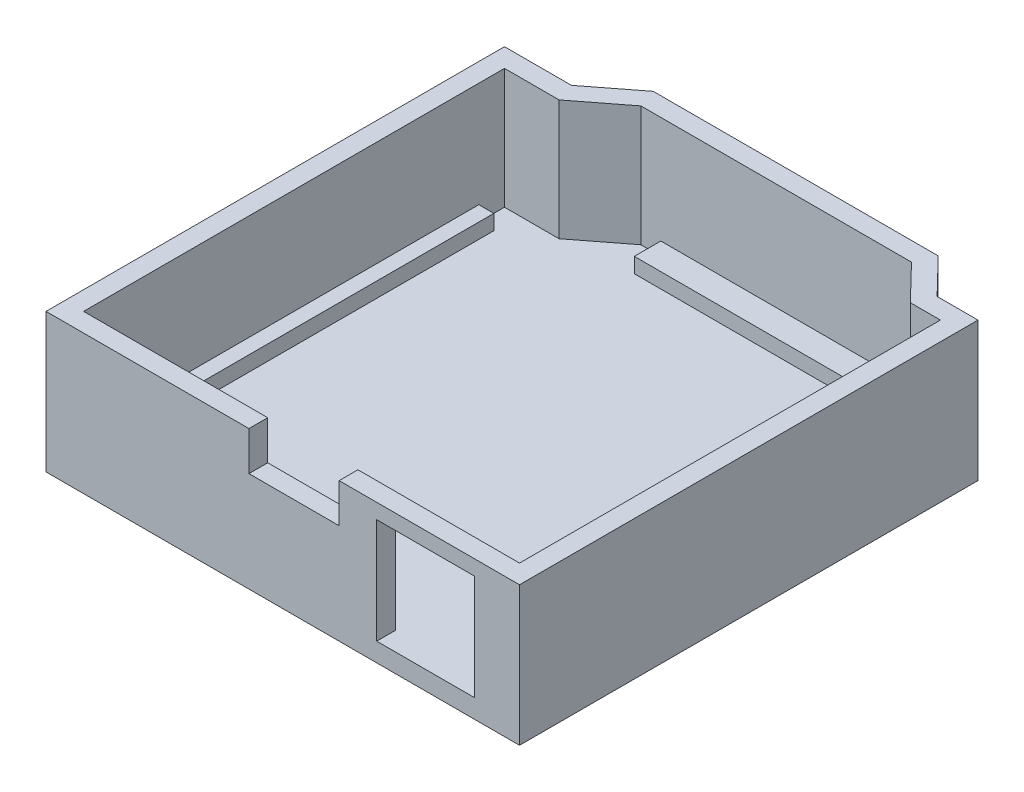
SolidWorks part; units mm, degrees
ref_plane "Front Plane" through (0, 0, 0) normal (0, 0, 1) x (1, 0, 0)
ref_plane "Top Plane" through (0, 0, 0) normal (0, 1, 0) x (1, 0, 0)
ref_plane "Right Plane" through (0, 0, 0) normal (1, 0, 0) x (0, 0, -1)
sketch "Sketch1" plane through (0, 0, 0) normal (0, 1, 0) x (1, 0, 0)
  line L0 (0, 0) -> (0, 56)
  line L1 (0, 56) -> (7.2606, 56)
  line L2 (7.2606, 56) -> (13.3994, 60.7502)
  line L3 (13.3994, 60.7502) -> (49.3994, 60.7502)
  line L4 (0, 0) -> (58, 0)
  line L5 (58, 0) -> (58, 56)
  line L7 (58, 56) -> (54, 56)
  line L8 (54, 56) -> (49.3994, 60.7502)
  point P8 (7.2606, 56)
  point P10 (13.3994, 60.7502)
  dimension "D1" = 56
  dimension "D2" = 58
  dimension "D3" = 4
  dimension "D4" = 36
extrude "Boss-Extrude1" add sketch "Sketch1" along normal blind 16
shell "Shell1" thickness 2.5
sketch "Sketch2" plane through (0, 0, 0) normal (0, 0, -1) x (-1, 0, 0)
  line L5 (2.5, -2.5) -> (-60.5, -2.5) construction
  line L10 (-60.5, 16) -> (-60.5, -2.5) construction
  line L11 (-41.5, 14) -> (-54.5, 14)
  line L12 (-41.5, 14) -> (-41.5, 0)
  line L13 (-41.5, 0) -> (-54.5, 0)
  line L14 (-54.5, 14) -> (-54.5, 0)
  line L15 (2.5, 16) -> (-60.5, 16) construction
  line L16 (-24.5, 10.8048) -> (-36.5, 10.8048)
  line L17 (-24.5, 10.8048) -> (-24.5, 16)
  line L18 (-24.5, 16) -> (-36.5, 16)
  line L19 (-36.5, 10.8048) -> (-36.5, 16)
  dimension "D1" = 2.5
  dimension "D2" = 36
  dimension "D3" = 12
  dimension "D4" = 6
  dimension "D5" = 13
extrude "Cut-Extrude1" cut sketch "Sketch2" against normal blind 4
sketch "Sketch3" plane through (0, 0, 0) normal (0, 1, 0) x (1, 0, 0)
  line L0 (0, 56) -> (0, 0) construction
  line L1 (0, 52.5835) -> (2, 52.5835)
  line L2 (0, 52.5835) -> (0, 2.5835)
  line L3 (0, 2.5835) -> (2, 2.5835)
  line L4 (2, 52.5835) -> (2, 2.5835)
  line L7 (57.8762, 52.5835) -> (56.0617, 52.5835)
  line L8 (57.8762, 2.5835) -> (56.0617, 2.5835)
  line L9 (56.0617, 52.5835) -> (56.0617, 2.5835)
  line L10 (57.8762, 52.5835) -> (57.8762, 2.5835)
  point P14 (1.9531, 52.4762)
  dimension "D1" = 2
  dimension "D2" = 50
extrude "Boss-Extrude2" add sketch "Sketch3" along normal blind 2
sketch "Sketch4" plane through (0, 0, 0) normal (0, 1, 0) x (1, 0, 0)
  line L1 (16.2938, 60.5067) -> (47.3114, 60.5067)
  line L2 (16.2938, 60.5067) -> (16.2938, 56.9763)
  line L3 (16.2938, 56.9763) -> (47.3114, 56.9763)
  line L4 (47.3114, 60.5067) -> (47.3114, 56.9763)
  point P4 (49.581, 67.5676)
  point P5 (47.3114, 60.7502)
extrude "Boss-Extrude3" add sketch "Sketch4" along normal blind 2
